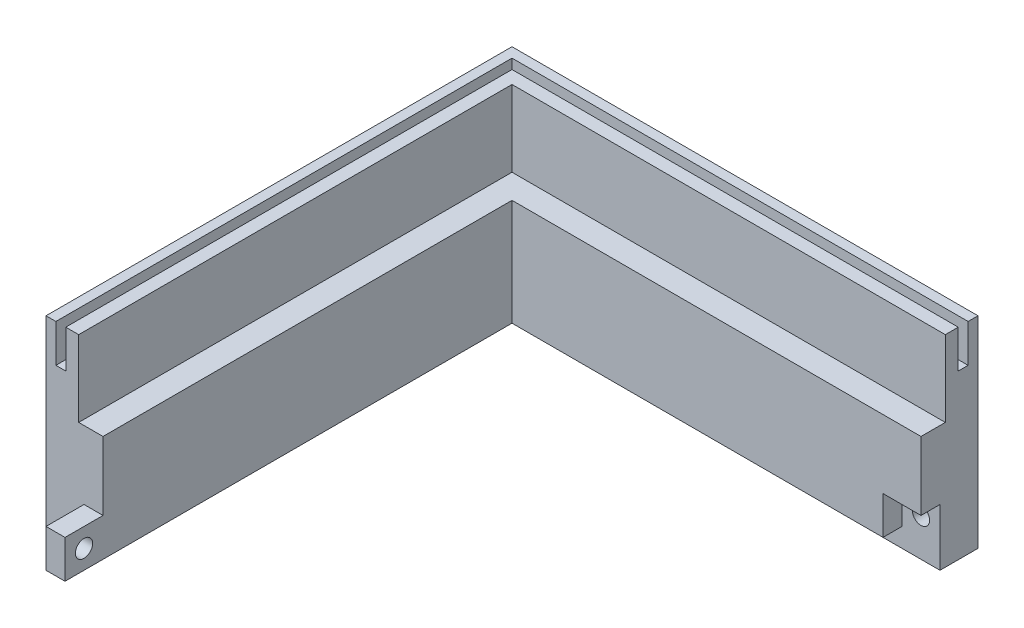
SolidWorks part; units mm, degrees
other "Markup1"
sketch "Sketch22" plane through (95.0964, 67.31, 130.7385) normal (0.1342, 0.9708, 0.1987) x (0.9567, -0.0747, -0.2814)
ref_plane "Front Plane" through (0, 0, 0) normal (0, 0, 1) x (1, 0, 0)
ref_plane "Top Plane" through (0, 0, 0) normal (0, 1, 0) x (1, 0, 0)
ref_plane "Right Plane" through (0, 0, 0) normal (1, 0, 0) x (0, 0, -1)
sketch "Sketch1" plane through (0, 0, 0) normal (0, 1, 0) x (1, 0, 0)
  line L7 (-60.6056, 37.6635) -> (95.0964, 37.6635)
  line L12 (95.0964, 37.6635) -> (95.0964, 18.6135)
  line L13 (95.0964, 18.6135) -> (-41.5556, 18.6135)
  line L14 (-41.5556, 18.6135) -> (-41.5556, -118.0385)
  line L15 (-41.5556, -118.0385) -> (-60.6056, -118.0385)
  line L16 (-60.6056, -118.0385) -> (-60.6056, 37.6635)
  line L17 (-57.3036, -118.0385) -> (-57.3036, 34.3615)
  line L18 (-57.3036, 34.3615) -> (95.0964, 34.3615)
  line L19 (-54.0016, -118.0385) -> (-54.0016, 31.0595)
  line L20 (-54.0016, 31.0595) -> (95.0964, 31.0595)
  line L21 (95.0964, 27.7575) -> (-50.6996, 27.7575)
  line L22 (-50.6996, 27.7575) -> (-50.6996, -118.0385)
  dimension "D1" = 155.702
  dimension "D2" = 19.05
  dimension "D3" = 3.302
  dimension "D4" = 3.302
  dimension "D5" = 3.302
extrude "Boss-Extrude5" add sketch "Sketch1" along normal blind 67.31 contours L14 L15 L16 L7 L12 L13
sketch "Sketch8" plane through (0, 67.31, 0) normal (0, 1, 0) x (1, 0, 0)
  line L0 (-57.3036, -118.0385) -> (-57.3036, 34.3615)
  line L1 (-57.3036, -118.0385) -> (-54.0016, -118.0385)
  line L2 (95.0964, 34.3615) -> (95.0964, 31.0595)
  line L3 (-41.5556, -118.0385) -> (-60.6056, -118.0385) construction
  line L4 (-57.3036, 34.3615) -> (95.0964, 34.3615)
  line L5 (95.0964, 37.6635) -> (95.0964, 18.6135) construction
  line L6 (-60.6056, -118.0385) -> (-60.6056, 37.6635) construction
  line L7 (-54.0016, -118.0385) -> (-54.0016, 31.0595)
  line L8 (-54.0016, 31.0595) -> (95.0964, 31.0595)
  dimension "D1" = 3.302
  dimension "D2" = 3.302
extrude "Cut-Extrude2" cut sketch "Sketch8" against normal blind 12.6933
sketch "Sketch9" plane through (0, 67.31, 0) normal (0, 1, 0) x (1, 0, 0)
  line L0 (-49.6836, -118.0385) -> (-49.6836, 26.7415)
  line L1 (-41.5556, -118.0385) -> (-54.0016, -118.0385) construction
  line L2 (-49.6836, 26.7415) -> (95.0964, 26.7415)
  line L3 (95.0964, 31.0595) -> (95.0964, 18.6135) construction
  line L4 (95.0964, 26.7415) -> (95.0964, 18.6135)
  line L5 (95.0964, 18.6135) -> (-41.5556, 18.6135)
  line L6 (-41.5556, 18.6135) -> (-41.5556, -118.0385)
  line L7 (-41.5556, -118.0385) -> (-49.6836, -118.0385)
  dimension "D1" = 4.318
extrude "Cut-Extrude3" cut sketch "Sketch9" against normal blind 25.4
sketch "Sketch15" plane through (0, 0, 0) normal (0, -1, 0) x (1, 0, 0)
  line L0 (-41.5556, 118.0385) -> (-47.9056, 118.0385)
  line L1 (-41.5556, 118.0385) -> (-60.6056, 118.0385) construction
  line L2 (-47.9056, 118.0385) -> (-47.9056, -24.9635)
  line L3 (-47.9056, -24.9635) -> (95.0964, -24.9635)
  line L4 (95.0964, -37.6635) -> (95.0964, -18.6135) construction
  line L5 (95.0964, -24.9635) -> (95.0964, -18.6135)
  line L6 (95.0964, -18.6135) -> (-41.5556, -18.6135)
  line L7 (-41.5556, -18.6135) -> (-41.5556, 118.0385)
  dimension "D1" = 6.35
extrude "Cut-Extrude5" cut sketch "Sketch15" against normal blind 6.35
sketch "Sketch16" plane through (0, 0, 118.0385) normal (0, 0, 1) x (1, 0, 0)
  line L0 (-41.5556, 41.91) -> (-41.5556, 6.35) construction
  line L1 (-47.9056, 6.35) -> (-41.5556, 6.35)
  line L2 (-47.9056, 6.35) -> (-47.9056, 19.05)
  line L3 (-47.9056, 19.05) -> (-41.5556, 19.05)
  line L4 (-41.5556, 6.35) -> (-41.5556, 19.05)
  dimension "D1" = 12.7
extrude "Boss-Extrude6" add sketch "Sketch16" along normal blind 12.7
sketch "Sketch17" plane through (95.0964, 0, 0) normal (1, 0, 0) x (0, 0, -1)
  line L0 (18.6135, 41.91) -> (18.6135, 6.35) construction
  line L1 (24.9635, 6.35) -> (18.6135, 6.35)
  line L2 (24.9635, 6.35) -> (24.9635, 19.05)
  line L3 (24.9635, 19.05) -> (18.6135, 19.05)
  line L4 (18.6135, 6.35) -> (18.6135, 19.05)
  dimension "D1" = 12.7
extrude "Cut-Extrude6" cut sketch "Sketch17" against normal blind 12.7
sketch "Sketch18" plane through (-41.5556, 0, 0) normal (1, 0, 0) x (0, 0, -1)
  line L0 (-130.7385, 12.7) -> (-118.0385, 12.7)
  line L1 (-118.0385, 19.05) -> (-130.7385, 19.05)
  line L2 (-118.0385, 19.05) -> (-118.0385, 6.35)
  line L3 (-118.0385, 6.35) -> (-130.7385, 6.35)
  line L4 (-130.7385, 19.05) -> (-130.7385, 6.35)
  line L5 (-124.3885, 19.05) -> (-124.3885, 6.35)
  circle A0 centre (-124.3885, 12.7) radius 2.8829
  dimension "D1" = 5.7658
extrude "Cut-Extrude7" cut sketch "Sketch18" against normal blind 12.7 contours A0
sketch "Sketch19" plane through (0, 0, -24.9635) normal (0, 0, 1) x (1, 0, 0)
  line L0 (95.0964, 12.7) -> (82.3964, 12.7)
  line L1 (82.3964, 6.35) -> (95.0964, 6.35)
  line L2 (82.3964, 6.35) -> (82.3964, 19.05)
  line L3 (82.3964, 19.05) -> (95.0964, 19.05)
  line L4 (95.0964, 6.35) -> (95.0964, 19.05)
  circle A0 centre (88.7464, 12.7) radius 2.8829
  dimension "D1" = 5.7658
extrude "Cut-Extrude8" cut sketch "Sketch19" against normal blind 4.826 contours A0
sketch "Sketch21" plane through (0, 6.35, 0) normal (0, -1, 0) x (1, 0, 0)
  line L0 (-41.5556, -18.6135) -> (-47.9056, -24.9635)
  circle A0 centre (-44.7306, -21.7885) radius 2.8829
  dimension "D1" = 5.7658
extrude "Cut-Extrude9" cut sketch "Sketch21" against normal blind 4.826 contours A0
